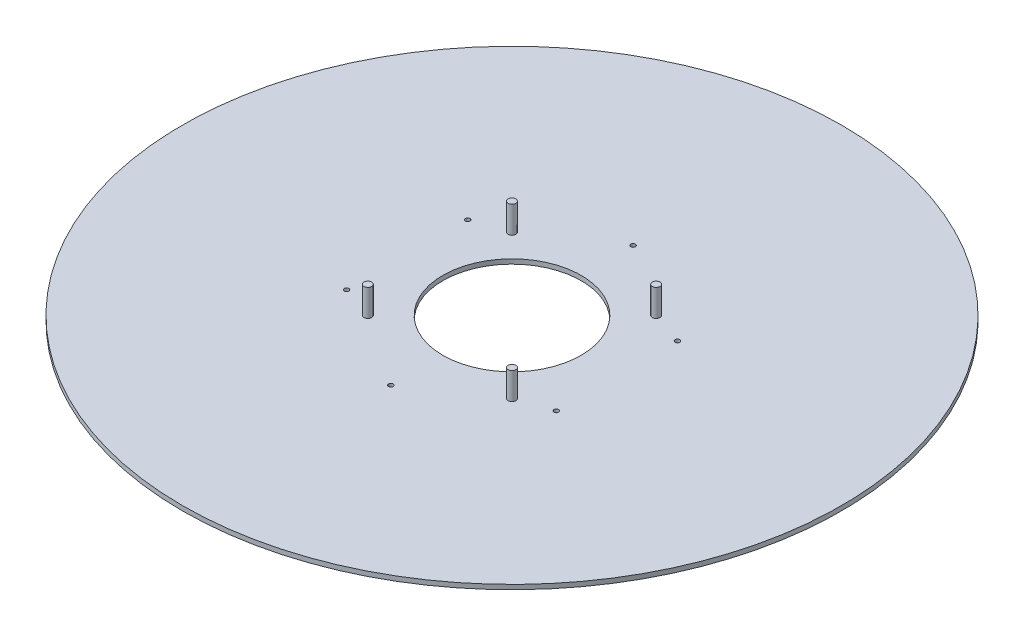
SolidWorks part; units mm, degrees
material "ASTM A36 Steel"
ref_plane "Front Plane" through (0, 0, 0) normal (0, 0, 1) x (1, 0, 0)
ref_plane "Top Plane" through (0, 0, 0) normal (0, 1, 0) x (1, 0, 0)
ref_plane "Right Plane" through (0, 0, 0) normal (1, 0, 0) x (0, 0, -1)
sketch "Sketch1" plane through (0, 0, 0) normal (0, 1, 0) x (1, 0, 0)
  circle A0 centre (0, 0) radius 428.5
  circle A1 centre (0, 0) radius 90
  dimension "D1" = 857
  dimension "D2" = 180
extrude "Boss-Extrude1" add sketch "Sketch1" along normal blind 6
sketch "Sketch2" plane through (0, 6, 0) normal (0, 1, 0) x (1, 0, 0)
  line L0 (0, 0) -> (0, 180.2166) construction
  circle A0 centre (0, 0) radius 157.5 construction
  circle A1 centre (0, 157.5) radius 3
  dimension "D1" = 315
  dimension "D2" = 6
extrude "Cut-Extrude1" cut sketch "Sketch2" against normal blind 6
sketch "Sketch5" plane through (0, 6, 0) normal (0, 1, 0) x (1, 0, 0)
  line L1 (0, 0) -> (93.6916, 0) construction
  line L2 (0, 0) -> (0, 93.6916) construction
  line L3 (0, 93.6916) -> (93.6916, 93.6916) construction
  line L4 (93.6916, 0) -> (93.6916, 93.6916) construction
  circle A0 centre (93.6916, 93.6916) radius 5
  circle A1 centre (0, 0) radius 132.5 construction
  dimension "D2" = 10
  dimension "D1" = 265
extrude "Boss-Extrude2" add sketch "Sketch5" along normal blind 35 contours A0
pattern_circular "CirPattern1" count 6 every 60 about axis through (0, 0, 0) along (0, 1, 0) of "Cut-Extrude1"
pattern_circular "CirPattern2" count 4 over 360 about axis through (0, 0, 0) along (0, 1, 0) of "Boss-Extrude2"
